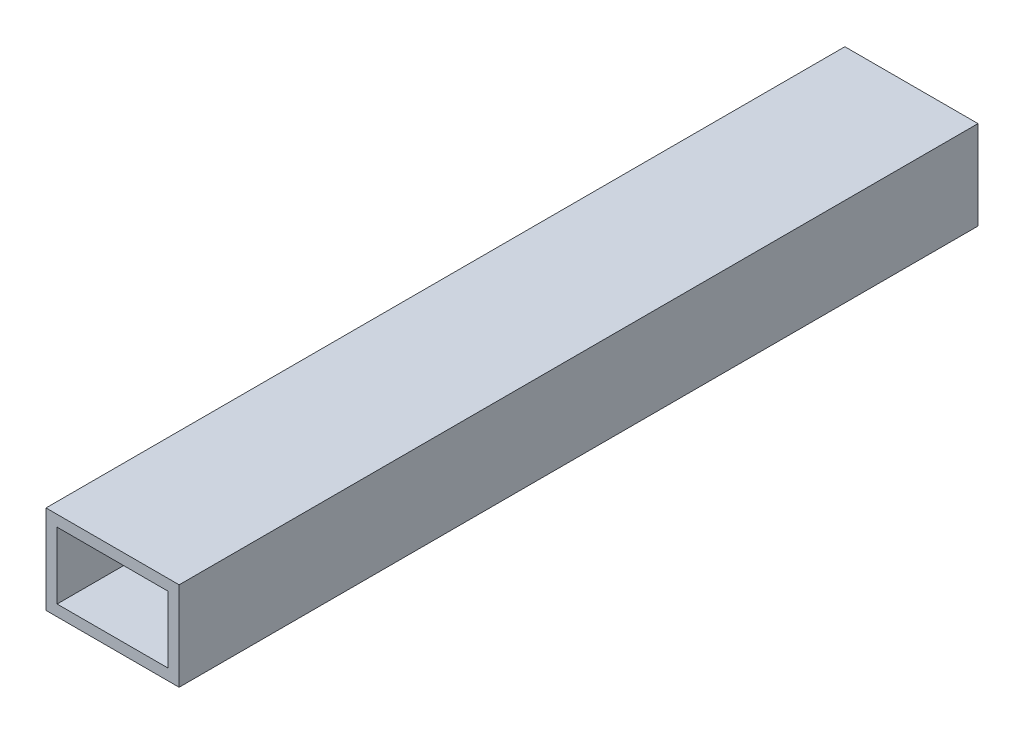
SolidWorks part; units mm, degrees
material "6061 Alloy"
ref_plane "Front Plane" through (0, 0, 0) normal (0, 0, 1) x (1, 0, 0)
ref_plane "Top Plane" through (0, 0, 0) normal (0, 1, 0) x (1, 0, 0)
ref_plane "Right Plane" through (0, 0, 0) normal (1, 0, 0) x (0, 0, -1)
sketch "Sketch1" plane through (0, 0, 0) normal (0, 0, 1) x (1, 0, 0)
  line L0 (19.05, 0) -> (15.875, 0) construction
  line L1 (-19.05, 0) -> (19.05, 0) construction
  line L2 (0, 12.7) -> (0, -12.7)
  point P7 (0, 0)
sketch "Sketch2" plane through (0, 0, 0) normal (1, 0, 0) x (0, 0, -1)
  line L0 (114.3, 0) -> (-114.3, 0)
  point P4 (0, 0)
  dimension "Length" = 228.6
sketch "Sketch3" plane through (0, 0, 0) normal (0, 0, 1) x (1, 0, 0)
  line L0 (-19.05, 0) -> (19.05, 0) construction
  line L5 (19.05, -12.7) -> (-19.05, -12.7)
  line L6 (19.05, -12.7) -> (19.05, 12.7)
  line L11 (19.05, 12.7) -> (-19.05, 12.7)
  line L12 (-19.05, -12.7) -> (-19.05, 12.7)
  line L14 (19.05, -12.7) -> (-19.05, 12.7) construction
  line L15 (19.05, 12.7) -> (-19.05, -12.7) construction
  line L16 (15.875, -9.525) -> (-15.875, -9.525)
  line L17 (15.875, -9.525) -> (15.875, 9.525)
  line L18 (15.875, 9.525) -> (-15.875, 9.525)
  line L19 (-15.875, -9.525) -> (-15.875, 9.525)
  line L20 (15.875, -9.525) -> (-15.875, 9.525) construction
  line L21 (15.875, 9.525) -> (-15.875, -9.525) construction
  point P0 (0, 0)
  point P5 (0, 0)
  point P13 (15.875, -12.7)
  dimension "D1" = 3.175
  dimension "D3" = 38.1
  dimension "D4" = 25.4
  dimension "D2" = 3.175
extrude "Boss-Extrude1" add sketch "Sketch3" along normal up to vertex (114.3 mm away) and the other way up to vertex (114.3 mm away) up to point (0, 0, 114.3) other way up to point (0, 0, -114.3)
sketch "Sketch5" plane through (0, 0, 0) normal (1, 0, 0) x (0, 0, -1)
  line L0 (-114.3, 0) -> (114.3, 0) construction
  line L3 (-114.3, -12.7) -> (-114.3, 12.7) construction
  line L4 (114.3, -12.7) -> (114.3, 12.7) construction
  point P6 (-71.4375, 0)
  point P7 (-57.15, 0)
  point P8 (57.15, 0)
  point P10 (71.4375, 0)
  dimension "D1" = 42.8625
  dimension "D2" = 57.15
  dimension "D3" = 42.8625
  dimension "D4" = 57.15
equation "\"D1@Sketch3\"=\"Wall thickness@Sketch1\""
equation "\"D1@Sketch5\"=\"Width@Sketch1\"*1.125"
equation "\"D2@Sketch5\"=\"Width@Sketch1\"*1.5"
equation "\"D3@Sketch5\"=\"D1@Sketch5\""
equation "\"D4@Sketch5\"=\"D2@Sketch5\""
equation "\"D2@Sketch3\"=\"Wall Thickness@Sketch1\""
